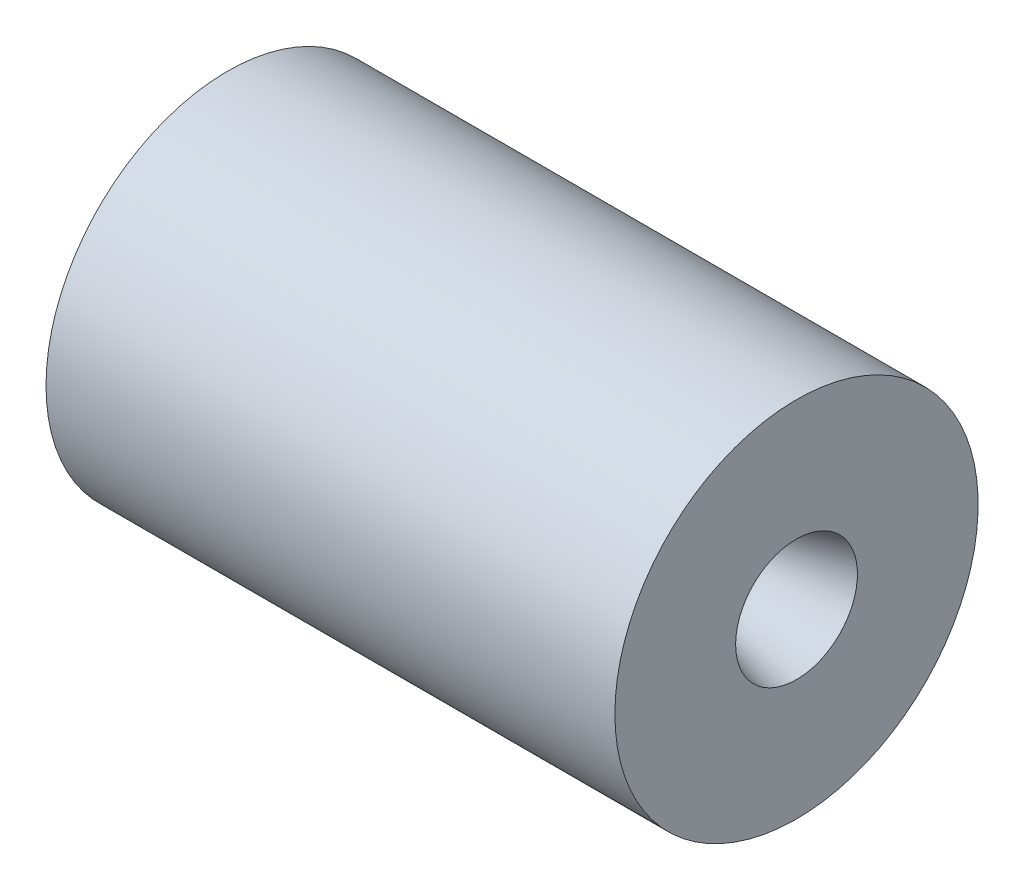
SolidWorks part; units mm, degrees
material "S-Glass Fiber"
ref_plane "Front Plane" through (0, 0, 0) normal (0, 0, 1) x (1, 0, 0)
ref_plane "Top Plane" through (0, 0, 0) normal (0, 1, 0) x (1, 0, 0)
ref_plane "Right Plane" through (0, 0, 0) normal (1, 0, 0) x (0, 0, -1)
sketch "Sketch1" plane through (0, 0, 0) normal (0, 0, 1) x (1, 0, 0)
  line L0 (-50.8993, 0) -> (36.1756, 0) construction
  line L1 (-57.483, 19.05) -> (-18.9264, 19.05)
  line L2 (-11.406, 15.3303) -> (-3.6762, 5.207)
  line L3 (0.8218, 3.4544) -> (18.172, 8.1007)
  line L4 (0, 0) -> (0, 3.3528) construction
  line L5 (-57.483, 19.05) -> (-57.483, 24.1554)
  line L6 (-57.483, 24.1554) -> (18.172, 24.1554)
  line L7 (18.172, 24.1554) -> (18.172, 8.1007)
  arc A0 (-18.9264, 19.05) -> (-11.406, 15.3303) centre (-18.9264, 9.5879) cw
  arc A1 (-3.6762, 5.207) -> (0, 3.3528) centre (0.0737, 8.0703) ccw
  arc A2 (0, 3.3528) -> (0.8218, 3.4544) centre (0.0468, 6.3482) ccw
  dimension "D1" = 19.05
  dimension "D2" = 57.483
  dimension "D3" = 15.3303
  dimension "D4" = 3.3528
  dimension "D5" = 5.207
  dimension "D6" = 11.406
  dimension "D7" = 0.8218
  dimension "D8" = 18.172
  dimension "D9" = 8.1007
  dimension "D10" = 3.4544
  dimension "D11" = 48.3108
revolve "Revolve1" add sketch "Sketch1" angle 360 about L0
equation "\"inj_x\"= 2.2631102214914933"
equation "\"inj_y\"= 0.7499999999999999"
equation "\"b_x\"= 0.9290244831013201"
equation "\"b_y\"= 0.7499999999999999"
equation "\"c_x\"= 0.5754710925080464"
equation "\"c_y\"= 0.6035533905932737"
equation "\"d_x\"= 0.1767766952966369"
equation "\"d_y\"= 0.20485899338186422"
equation "\"o_x\"= 0.0"
equation "\"o_y\"= 0.13163568867850112"
equation "\"n_x\"= 0.03235238063781509"
equation "\"n_y\"= 0.1358941362361297"
equation "\"e_x\"= 0.7154340612147704"
equation "\"e_y\"= 0.318925320911219"
equation "\"D1@Sketch1\"=\"inj_y\""
equation "\"D2@Sketch1\"=\"inj_x\""
equation "\"D3@Sketch1\"=\"c_y\""
equation "\"D7@Sketch1\"=\"n_x\""
equation "\"D8@Sketch1\"=\"e_x\""
equation "\"D9@Sketch1\"=\"e_y\""
